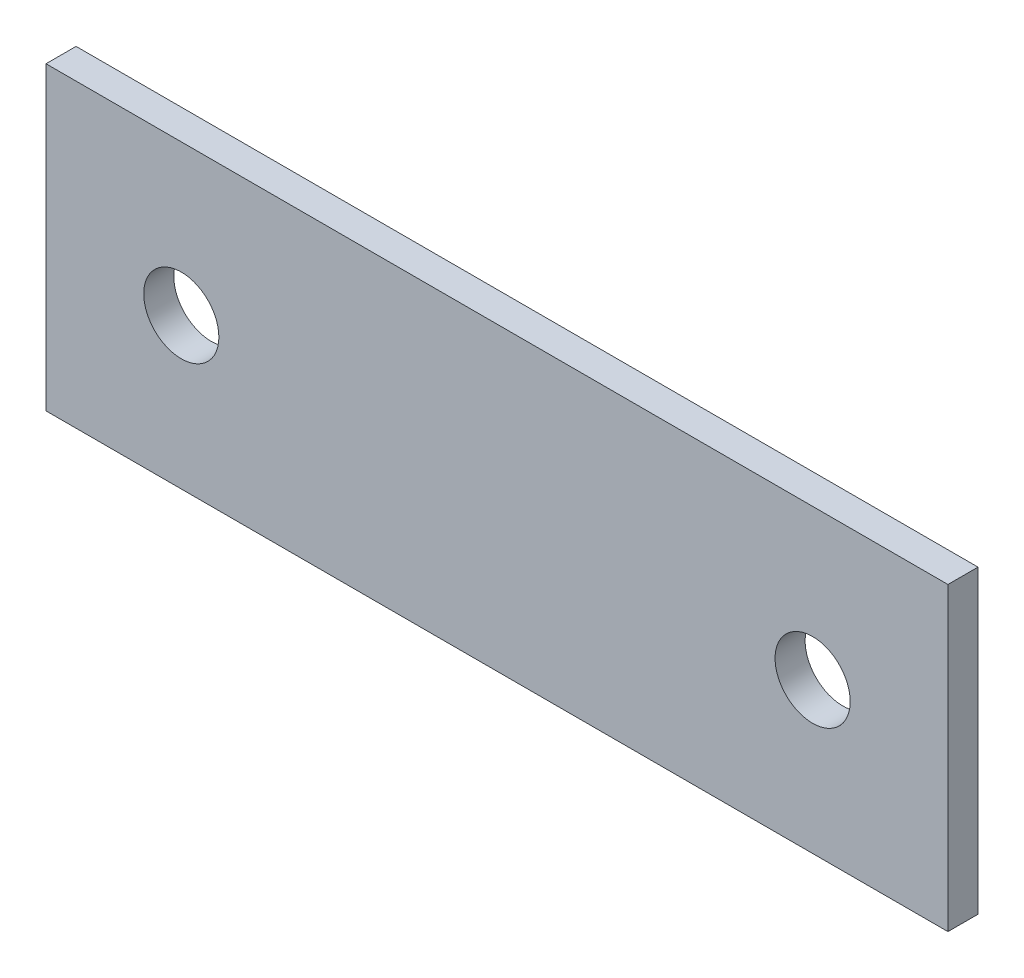
SolidWorks part; units mm, degrees
ref_plane "前视基准面" through (0, 0, 0) normal (0, 0, 1) x (1, 0, 0)
ref_plane "上视基准面" through (0, 0, 0) normal (0, 1, 0) x (1, 0, 0)
ref_plane "右视基准面" through (0, 0, 0) normal (1, 0, 0) x (0, 0, -1)
sketch "草图1" plane through (0, 0, 0) normal (0, 0, 1) x (1, 0, 0)
  line L0 (-30, 0) -> (30, 0) construction
  line L1 (30, 10) -> (-30, 10)
  line L2 (30, 10) -> (30, -10)
  line L3 (30, -10) -> (-30, -10)
  line L4 (-30, 10) -> (-30, -10)
  line L5 (0, 10) -> (0, -10) construction
  circle A0 centre (-21, 0) radius 2.5
  circle A1 centre (21, 0) radius 2.5
  point P0 (0, 0)
  dimension "D3" = 42
  dimension "D1" = 20
  dimension "D2" = 60
  dimension "D4" = 9
extrude "凸台-拉伸1" add sketch "草图1" along normal blind 2
